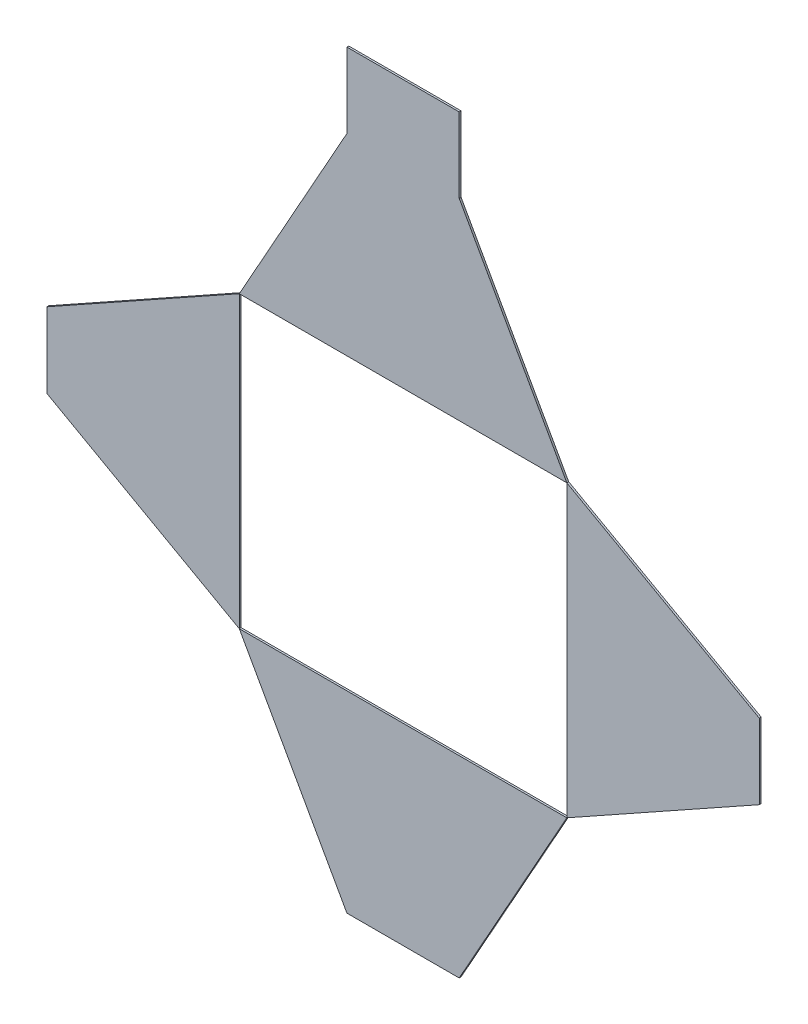
SolidWorks part; units mm, degrees
ref_plane "Front Plane" through (0, 0, 0) normal (0, 0, 1) x (1, 0, 0)
ref_plane "Top Plane" through (0, 0, 0) normal (0, 1, 0) x (1, 0, 0)
ref_plane "Right Plane" through (0, 0, 0) normal (1, 0, 0) x (0, 0, -1)
sketch "Sketch1" plane through (0, 0, 0) normal (0, 0, 1) x (1, 0, 0)
  line L0 (380.7413, 40) -> (380.7413, -40)
  line L1 (175, -155) -> (-175, -155)
  line L2 (175, -155) -> (175, 155)
  line L3 (175, 155) -> (-175, 155)
  line L4 (-175, -155) -> (-175, 155)
  line L5 (175, -155) -> (-175, 155) construction
  line L6 (175, 155) -> (-175, -155) construction
  line L7 (175, 155) -> (380.7413, 40)
  line L8 (380.7413, -40) -> (175, -155)
  line L9 (0, 155) -> (0, -155) construction
  line L10 (-380.7413, -40) -> (-175, -155)
  line L11 (-380.7413, 40) -> (-380.7413, -40)
  line L12 (-175, 155) -> (-380.7413, 40)
  line L13 (-175, 0) -> (175, 0) construction
  line L14 (-60, 360.7413) -> (60, 360.7413)
  line L15 (0, 155) -> (0, 360.7413) construction
  line L16 (-60, 360.7413) -> (-175, 155)
  line L17 (60, 360.7413) -> (175, 155)
  line L18 (-60, -360.7413) -> (-175, -155)
  line L19 (60, -360.7413) -> (175, -155)
  line L20 (-60, -360.7413) -> (60, -360.7413)
  line L21 (-60, 360.7413) -> (-60, 440.7413)
  line L22 (-60, 440.7413) -> (60, 440.7413)
  line L23 (60, 440.7413) -> (60, 360.7413)
  point P0 (0, 0)
  dimension "D1" = 350
  dimension "D2" = 310
  dimension "D3" = 80
  dimension "D4" = 235.7
  dimension "D5" = 235.7
  dimension "D6" = 120
  dimension "D7" = 235.7
  dimension "D8" = 80
extrude "Boss-Extrude2" add sketch "Sketch1" along normal blind 2 contours L23 L22 L21 L14 | L17 L14 L16 L3 | L8 L0 L7 L2 | L18 L20 L19 L1 | L4 L12 L11 L10
